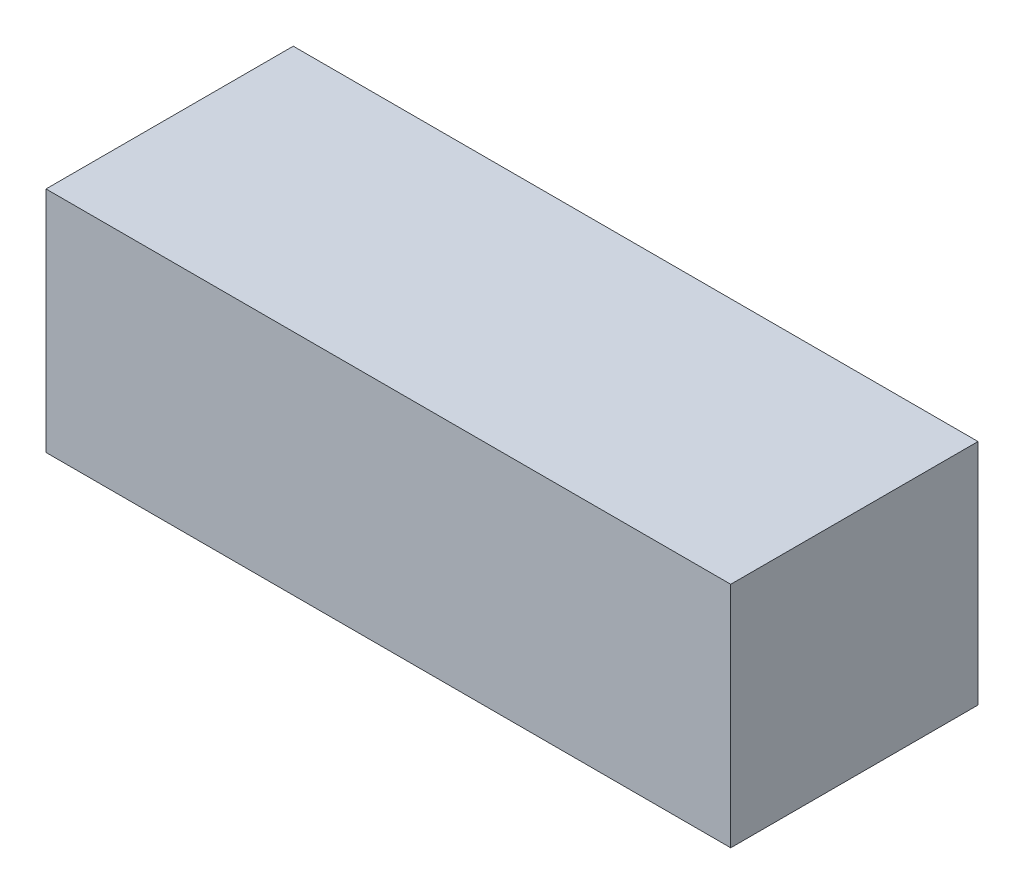
SolidWorks part; units mm, degrees
ref_plane "Спереди" through (0, 0, 0) normal (0, 0, 1) x (1, 0, 0)
ref_plane "Сверху" through (0, 0, 0) normal (0, 1, 0) x (1, 0, 0)
ref_plane "Справа" through (0, 0, 0) normal (1, 0, 0) x (0, 0, -1)
other "Configuration Table"
sketch "Эскиз1" plane through (0, 0, 0) normal (0, 1, 0) x (1, 0, 0)
  line L1 (-90, -32.5) -> (90, -32.5)
  line L2 (-90, -32.5) -> (-90, 32.5)
  line L3 (-90, 32.5) -> (90, 32.5)
  line L4 (90, -32.5) -> (90, 32.5)
  line L5 (-90, -32.5) -> (90, 32.5) construction
  line L6 (-90, 32.5) -> (90, -32.5) construction
  point P0 (0, 0)
  dimension "D1" = 65
  dimension "D2" = 180
extrude "Бобышка-Вытянуть1" add sketch "Эскиз1" along normal blind 60
